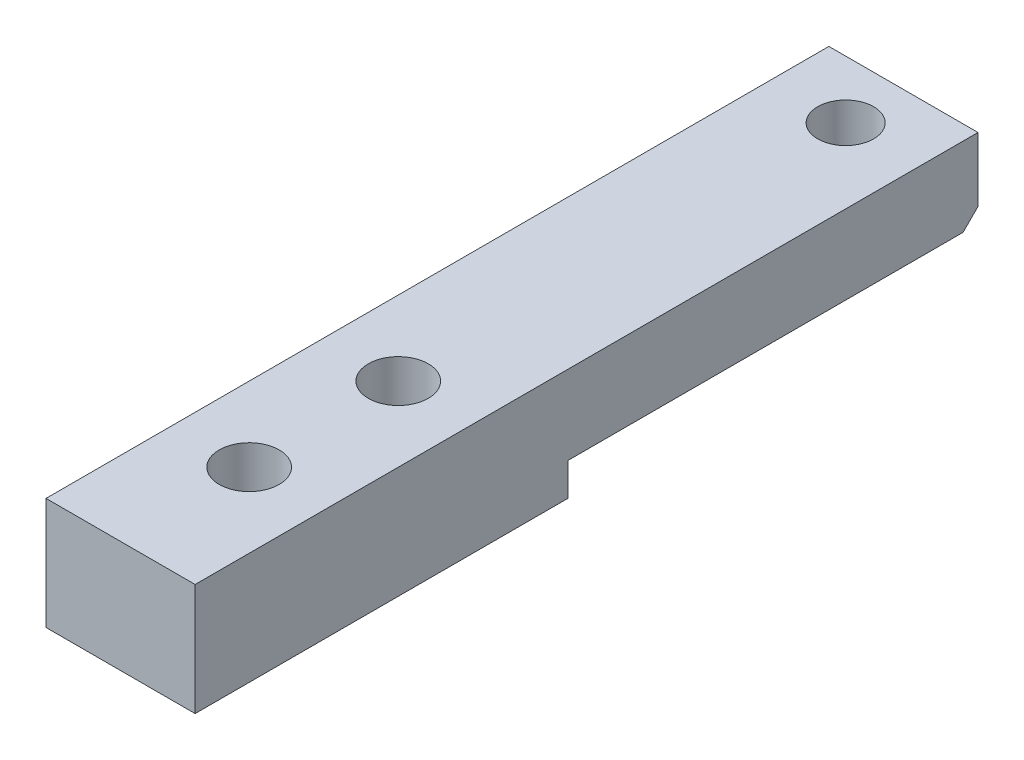
SolidWorks part; units mm, degrees
material "6061-T6 (SS)"
ref_plane "Front Plane" through (0, 0, 0) normal (0, 0, 1) x (1, 0, 0)
ref_plane "Top Plane" through (0, 0, 0) normal (0, 1, 0) x (1, 0, 0)
ref_plane "Right Plane" through (0, 0, 0) normal (1, 0, 0) x (0, 0, -1)
sketch "Sketch1" plane through (0, 0, 0) normal (1, 0, 0) x (0, 0, -1)
  line L1 (0, 0) -> (31.75, 0)
  line L2 (0, 0) -> (0, 9.525)
  line L3 (0, 9.525) -> (66.675, 9.525)
  line L4 (31.75, 0) -> (31.75, 2.794)
  line L7 (31.75, 2.794) -> (66.675, 2.794)
  line L8 (66.675, 9.525) -> (66.675, 2.794)
  dimension "D1" = 2.794
  dimension "D2" = 34.925
  dimension "D3" = 9.525
  dimension "D4" = 31.75
extrude "Boss-Extrude1" add sketch "Sketch1" along normal mid plane 12.7
hole_wizard "#10 Clearance Hole1" positions "Sketch2" profile "Sketch3" hole size "#10" standard "ANSI Inch" end condition through all
sketch "Sketch2" plane through (0, 0, 0) normal (0, -1, 0) x (-1, 0, 0)
  line L1 (-6.35, 0) -> (-6.35, 31.75) construction
  line L3 (-6.35, 0) -> (6.35, 0) construction
  line L4 (0, 23.6538) -> (0, 10.9538) construction
  line L8 (-6.35, 31.75) -> (6.35, 31.75) construction
  point P0 (0, 23.6538)
  point P15 (0, 0)
  point P20 (0, 10.9538)
  dimension "D1" = 12.7
  dimension "D2" = 8.0962
sketch "Sketch3" plane through (0, 0, -23.6538) normal (1, 0, 0) x (0, 0, -1)
  line L0 (0, 0) -> (0, 9.525)
  line L1 (0, 9.525) -> (2.5527, 9.525)
  line L2 (2.5527, 9.525) -> (2.5527, 0)
  line L5 (2.5527, 0) -> (0, 0)
  line L11 (0, -6.35) -> (0, 107.95) construction
  dimension "Thru Hole Dia." = 5.1054
  dimension "Thru Hole Depth" = 9.525
sketch "Sketch4" plane through (0, 9.525, 0) normal (0, 1, 0) x (1, 0, 0)
  line L0 (0, 61.7538) -> (0, 23.6538) construction
  circle A0 centre (0, 61.7538) radius 2.3812
  dimension "D1" = 4.7625
  dimension "D2" = 38.1
extrude "Cut-Extrude1" cut sketch "Sketch4" against normal up to next
chamfer "Chamfer1" distance 1.27 angle 45 1 edges at (0, 2.794, -66.675)
